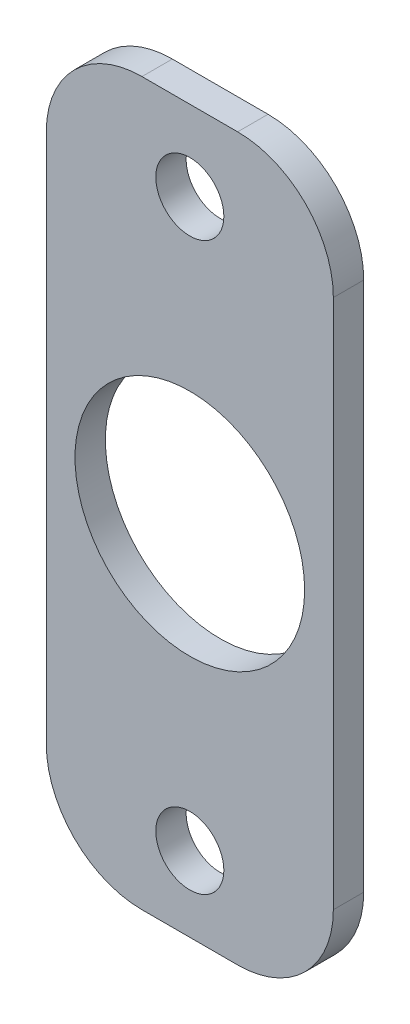
SolidWorks part; units mm, degrees
ref_plane "Front" through (0, 0, 0) normal (0, 0, 1) x (1, 0, 0)
ref_plane "Top" through (0, 0, 0) normal (0, 1, 0) x (1, 0, 0)
ref_plane "Right" through (0, 0, 0) normal (1, 0, 0) x (0, 0, -1)
sketch "Sketch1" plane through (0, 0, 0) normal (0, 0, 1) x (1, 0, 0)
  line L1 (-158.8932, 102.3639) -> (-57.2932, 102.3639)
  line L2 (-158.8932, 102.3639) -> (-158.8932, 0.7639)
  line L3 (-158.8932, 0.7639) -> (-57.2932, 0.7639)
  line L4 (-57.2932, 102.3639) -> (-57.2932, 0.7639)
  dimension "D1" = 101.6
  dimension "D2" = 101.6
extrude "Boss-Extrude1" add sketch "Sketch1" along normal blind 1.5875
sketch "Sketch2" plane through (0, 0, 1.5875) normal (0, 0, 1) x (1, 0, 0)
  circle A0 centre (-108.0932, 51.5639) radius 6
  circle A1 centre (-108.0932, 51.5639) radius 14.7963
  circle A2 centre (-119.1588, 61.3866) radius 2.9721
  dimension "D1" = 12
  dimension "D2" = 29.5927
extrude "Cut-Extrude1" cut sketch "Sketch2" against normal through all contours A0
sketch "Sketch4" plane through (0, 0, 1.5875) normal (0, 0, 1) x (1, 0, 0)
  circle A0 centre (-108.0932, 51.5639) radius 14.7963 construction
  circle A1 centre (-108.0932, 66.3602) radius 1.778
  circle A3 centre (-108.0932, 36.7676) radius 1.778
  dimension "D1" = 29.5927
  dimension "D2" = 3.556
  dimension "D3" = 3.556
extrude "Cut-Extrude2" cut sketch "Sketch4" against normal through all
sketch "Sketch5" plane through (0, 0, 1.5875) normal (0, 0, 1) x (1, 0, 0)
  line L4 (-158.8932, 0.7639) -> (-57.2932, 0.7639) construction
  line L6 (-57.2932, 102.3639) -> (-158.8932, 102.3639) construction
  line L8 (-158.8932, 102.3639) -> (-115.5932, 102.3639)
  line L9 (-158.8932, 102.3639) -> (-158.8932, 0.7639)
  line L10 (-158.8932, 0.7639) -> (-115.5932, 0.7639)
  line L11 (-115.5932, 102.3639) -> (-115.5932, 0.7639)
  line L13 (-57.2932, 102.3639) -> (-100.5932, 102.3639)
  line L14 (-57.2932, 102.3639) -> (-57.2932, 0.7639)
  line L15 (-57.2932, 0.7639) -> (-100.5932, 0.7639)
  line L16 (-100.5932, 102.3639) -> (-100.5932, 0.7639)
extrude "Cut-Extrude4" cut sketch "Sketch5" against normal through all
sketch "Sketch10" plane through (0, 0, 1.5875) normal (0, 0, 1) x (1, 0, 0)
  line L0 (-100.5932, 102.3639) -> (-100.5932, 0.7639) construction
  line L1 (-115.5932, 102.3639) -> (-100.5932, 102.3639)
  line L2 (-115.5932, 102.3639) -> (-115.5932, 70.5472)
  line L3 (-115.5932, 70.5472) -> (-100.5932, 70.5472)
  line L4 (-100.5932, 102.3639) -> (-100.5932, 70.5472)
  line L5 (-115.5932, 0.7639) -> (-115.5932, 102.3639) construction
  line L6 (-100.5932, 0.7639) -> (-115.5932, 0.7639)
  line L7 (-100.5932, 0.7639) -> (-100.5932, 32.8454)
  line L8 (-100.5932, 32.8454) -> (-115.5932, 32.8454)
  line L9 (-115.5932, 0.7639) -> (-115.5932, 32.8454)
extrude "Cut-Extrude5" cut sketch "Sketch10" against normal through all
fillet "Fillet1" radius 5 4 edges at (-100.5932, 70.5472, 0.7937) (-100.5932, 32.8454, 0.7937) (-115.5932, 32.8454, 0.7937) (-115.5932, 70.5472, 0.7937)
